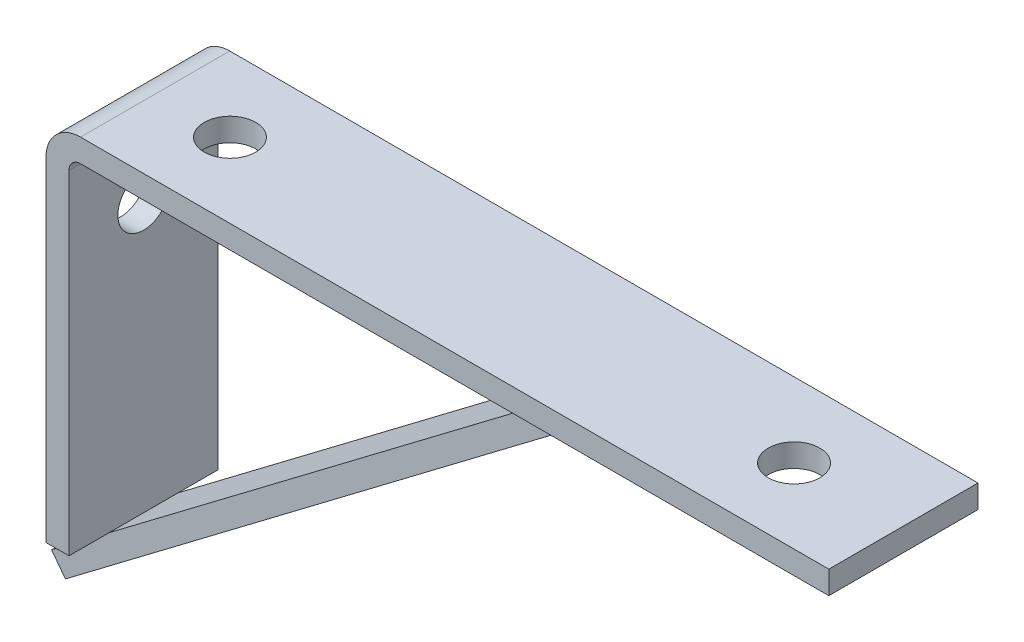
SolidWorks part; units mm, degrees
ref_plane "Front Plane" through (0, 0, 0) normal (0, 0, 1) x (1, 0, 0)
ref_plane "Top Plane" through (0, 0, 0) normal (0, 1, 0) x (1, 0, 0)
ref_plane "Right Plane" through (0, 0, 0) normal (1, 0, 0) x (0, 0, -1)
sketch "Sketch1" plane through (0, 0, 0) normal (0, 0, 1) x (1, 0, 0)
  line L0 (-112.7125, -101.6) -> (-112.7125, -9.525)
  line L1 (-103.1875, 0) -> (103.1875, 0)
  arc A0 (-112.7125, -9.525) -> (-103.1875, 0) centre (-103.1875, -9.525) cw
  point P6 (-112.7125, 0)
  dimension "D1" = 9.525
  dimension "LG" = 215.9
  dimension "HT" = 101.6
extrude "Extrude-Thin1" add sketch "Sketch1" along normal mid plane 41.148 thin
sketch "Sketch2" plane through (0, 0, 0) normal (0, 0, 1) x (1, 0, 0)
  line L0 (19.5676, -6.35) -> (-106.3625, -101.6)
  line L1 (-122.2375, -113.6074) -> (-118.4069, -118.6719)
  line L2 (-118.4069, -118.6719) -> (30.094, -6.35)
  line L3 (19.5676, -6.35) -> (30.094, -6.35)
  line L4 (-103.1875, -6.35) -> (103.1875, -6.35) construction
  line L5 (-106.3625, -101.6) -> (-112.7125, -101.6) construction
  line L6 (-106.3625, -101.6) -> (-112.7125, -101.6)
  line L7 (-112.7125, -101.6) -> (-112.7125, -106.403)
  line L8 (-112.7125, -106.403) -> (-122.2375, -113.6074)
  dimension "D1" = 6.35
  dimension "D2" = 9.525
  dimension "D3" = 177.8
extrude "Boss-Extrude1" add sketch "Sketch2" along normal mid plane 19.05
sketch "Sketch3" plane through (0, 0, 0) normal (0, 1, 0) x (1, 0, 0)
  line L0 (-82.55, 0) -> (73.025, 0) construction
  line L1 (-112.7125, -20.574) -> (-112.7125, 20.574) construction
  line L2 (103.1875, -20.574) -> (103.1875, 20.574) construction
  circle A0 centre (-82.55, 0) radius 7.112
  circle A2 centre (73.025, 0) radius 7.112
  dimension "D2" = 30.1625
  dimension "D5" = 14.224
  dimension "D1" = 30.1625
extrude "Cut-Extrude1" cut sketch "Sketch3" against normal blind 6.35
sketch "Sketch4" plane through (-112.7125, 0, 0) normal (-1, 0, 0) x (0, 0, 1)
  circle A0 centre (0, -26.9875) radius 7.112
  dimension "D1" = 14.224
  dimension "D2" = 26.9875
extrude "Cut-Extrude2" cut sketch "Sketch4" against normal blind 6.35
